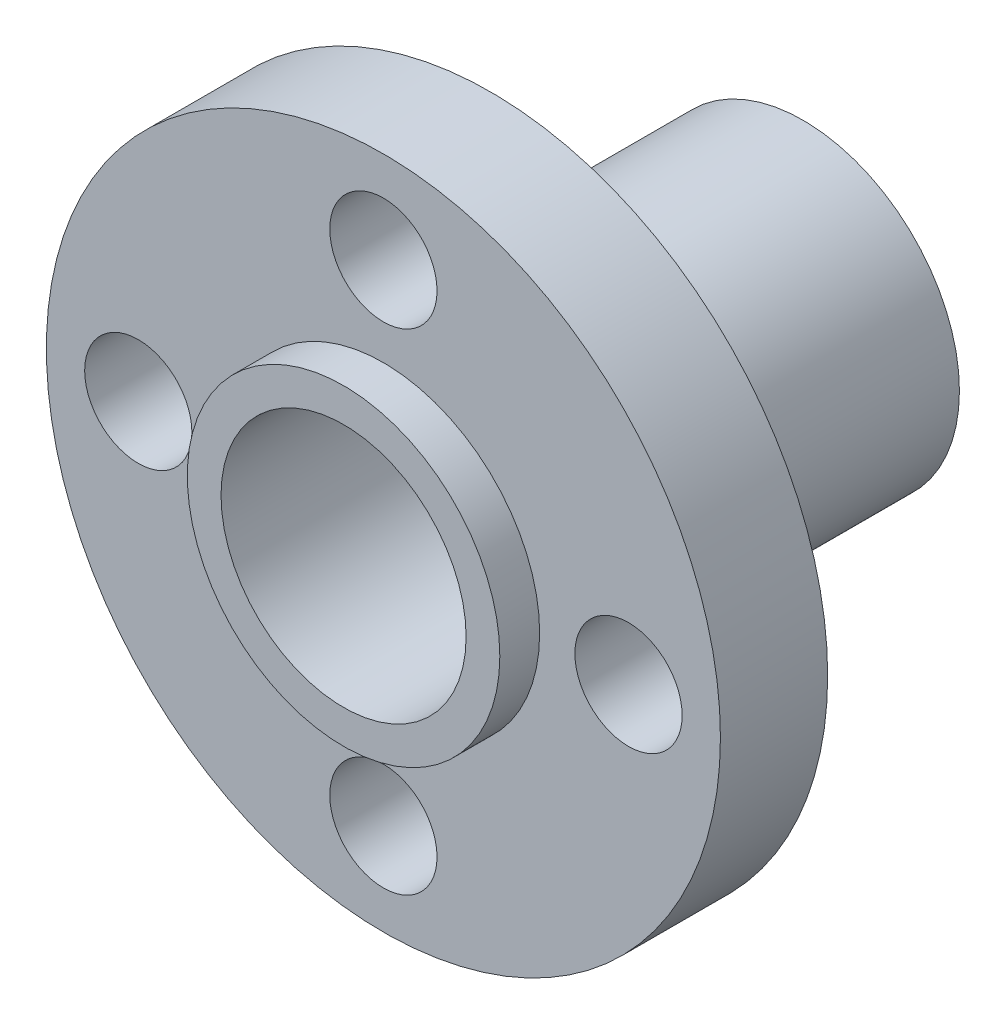
SolidWorks part; units mm, degrees
material "铜"
ref_plane "前视基准面" through (0, 0, 0) normal (0, 0, 1) x (1, 0, 0)
ref_plane "上视基准面" through (0, 0, 0) normal (0, 1, 0) x (1, 0, 0)
ref_plane "右视基准面" through (0, 0, 0) normal (1, 0, 0) x (0, 0, -1)
sketch "草图1" plane through (0, 0, 0) normal (0, 0, 1) x (1, 0, 0)
  circle A0 centre (0, 0) radius 4
  circle A1 centre (0, 0) radius 5.1
  dimension "D1" = 8
  dimension "D2" = 10.2
extrude "凸台-拉伸1" add sketch "草图1" along normal blind 15
sketch "草图2" plane through (0, 0, 15) normal (0, 0, 1) x (1, 0, 0)
  circle A0 centre (0, 0) radius 11
  circle A1 centre (0, 0) radius 5.1
  dimension "D1" = 22
extrude "凸台-拉伸2" add sketch "草图2" against normal blind 3.5 from offset 1.3 offset against normal yes
sketch "草图3" plane through (0, 0, 10.2) normal (0, 0, -1) x (-1, 0, 0)
  line L0 (0, 0) -> (8.298, 0) construction
  circle A0 centre (8, 0) radius 1.75
  circle A1 centre (0, -8) radius 1.75
  circle A2 centre (-8, 0) radius 1.75
  circle A3 centre (0, 8) radius 1.75
  point P2 (0, 0)
  point P7 (0, -1.1905)
  point P16 (0, 0)
  dimension "D1" = 3.5
  dimension "D2" = 8
  dimension "D4" = 8
  dimension "D3" = 4
extrude "切除-拉伸1" cut sketch "草图3" against normal blind 5
